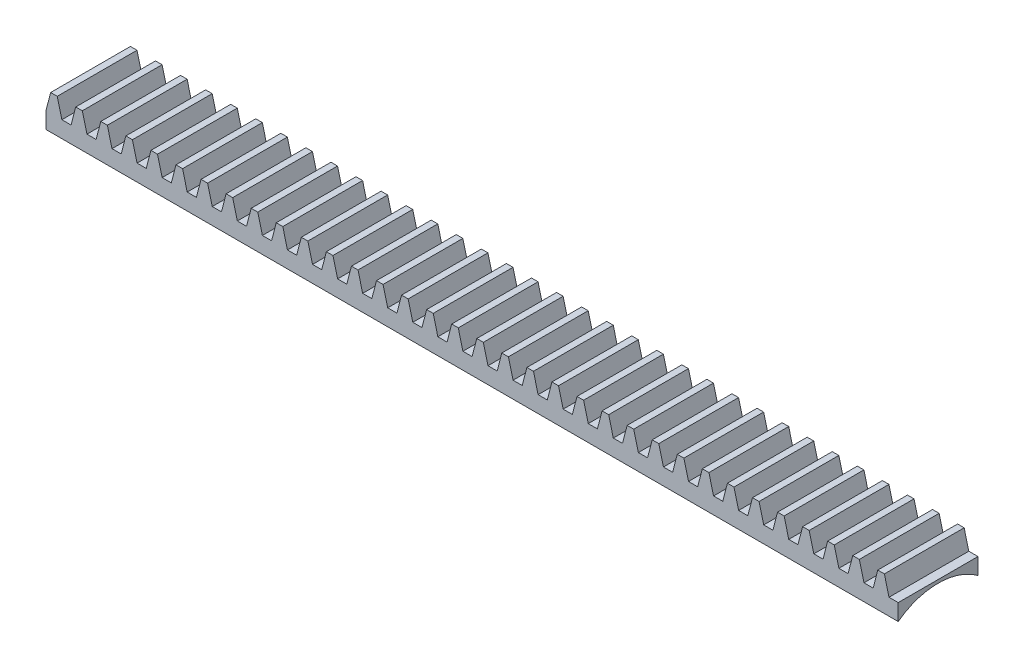
SolidWorks part; units mm, degrees
extrude "Blank" add sketch "BlankSke" against normal blind 10
sketch "BlankSke" plane through (0, 0, 0) normal (0, 0, 1) x (1, 0, 0)
  line L1 (0, 0) -> (110, 0)
  line L2 (0, 0) -> (0, 11)
  line L3 (0, 11) -> (110, 11)
  line L4 (110, 0) -> (110, 11)
  dimension "Length" = 110
  dimension "Blank_height" = 11
ref_plane "Plane1" through (0, 0, 0) normal (0, 0, 1) x (1, 0, 0)
ref_plane "Plane2" through (0, 0, 0) normal (0, 1, 0) x (1, 0, 0)
ref_plane "Plane3" through (0, 0, 0) normal (1, 0, 0) x (0, 0, -1)
sketch "HoldingSke" plane through (0, 0, 0) normal (0, 1, 0) x (1, 0, 0)
  line L0 (0, 0) -> (0.1392, 0.9903)
  line L1 (-15, 0) -> (100, 0) construction
  line L2 (0, 0) -> (-2.1039, 2.3779)
  line L3 (0, 0) -> (-11.863, 4.5341)
  line L4 (0, 0) -> (6.897, 5.1973)
  line L5 (0, 0) -> (-23.7986, -8.8762)
  line L6 (0, 0) -> (-10.5278, -7.1032)
  line L9 (-67.7845, 28.3722) -> (38.7117, 55.914)
  line L10 (-76.2, 3.3779) -> (-66.2, 3.3779)
  line L11 (0, 0) -> (-10, 0)
  line L12 (-76.2, 101.6) -> (-76.162, 101.6)
  line L13 (24.9733, 27.94) -> (52.9518, 28.4284)
  line L14 (24.9733, 27.94) -> (24.9743, 27.94)
  line L15 (24.9733, 27.94) -> (100.4006, 29.5858)
  circle A0 centre (0, 0) radius 19.05
  circle A1 centre (0, 0) radius 5
  circle A2 centre (0, 0) radius 12.7
  dimension "MPH" = 10
  dimension "Diameter" = 38.1
  dimension "Num_teeth" = 37
  dimension "Pitch" = 1
  dimension "Show_teeth" = 998
  dimension "Thickness" = 12.7
  dimension "Ap" = 14.5
  dimension "Pitch_height" = 10
  dimension "Width" = 10
  dimension "Backlash" = 0.038
  dimension "Addendum_fac" = 1
  dimension "Dedendum_fac" = 1.25
  dimension "Clearance_fac" = 0.25
  dimension "Dedendum_add" = 0.001
  dimension "Length" = 110
  dimension "Module" = 1
sketch "TooCutSkeIll" plane through (0, 0, 0) normal (0, 0, 1) x (1, 0, 0)
  line L0 (-1.1503, 10.97) -> (-0.6248, 8.9382)
  line L1 (-0.3818, 8.75) -> (0.3818, 8.75)
  line L2 (0.6248, 8.9382) -> (1.1503, 10.97)
  line L3 (110, 11) -> (0, 11) construction
  line L4 (0, 0) -> (0, 64.897) construction
  line L5 (-13.208, 10) -> (12.954, 10) construction
  line L6 (0, 0) -> (110, 0) construction
  line L7 (0.8994, 10) -> (0.8994, 48.7463) construction
  line L8 (-0.8994, 10) -> (-0.8994, 48.7463) construction
  line L9 (1.189, 11) -> (1.189, 11.0254)
  line L10 (-1.189, 11) -> (-1.189, 11.0254)
  line L11 (-1.189, 11.0254) -> (1.189, 11.0254)
  arc A0 (0.3818, 8.75) -> (0.6248, 8.9382) centre (0.3818, 9.001) ccw
  arc A1 (-0.6248, 8.9382) -> (-0.3818, 8.75) centre (-0.3818, 9.001) ccw
  arc A2 (1.189, 11) -> (1.1503, 10.97) centre (1.189, 10.96) ccw
  arc A3 (-1.1503, 10.97) -> (-1.189, 11) centre (-1.189, 10.96) ccw
  dimension "Pitch_height" = 10
  dimension "Addendum_plus" = 1.0254
  dimension "Pressure_angle" = 14.5
  dimension "Gap_width" = 1.7988
  dimension "Dedendum" = 1.25
extrude "ToothCutIll" [suppressed] cut sketch "TooCutSkeIll" against normal through all
sketch "TooCutSkeSim" plane through (0, 0, 0) normal (0, 0, 1) x (1, 0, 0)
  line L0 (0.5761, 8.75) -> (-0.5761, 8.75)
  line L1 (1.1646, 11.0254) -> (0.5761, 8.75)
  line L2 (0, 17.4625) -> (0, 53.467) construction
  line L3 (1.1646, 11.0254) -> (-1.1646, 11.0254)
  line L6 (-1.1646, 11.0254) -> (-0.5761, 8.75)
  line L9 (-0.8994, 10) -> (0.8994, 10) construction
  line L10 (0, 0) -> (110, 0) construction
  line L11 (0.8994, 10) -> (0.8994, 53.467) construction
  line L12 (-0.8994, 10) -> (-0.8994, 53.467) construction
  dimension "Pitch_height" = 10
  dimension "Addendum_plus" = 1.0254
  dimension "Pressure_angle" = 14.5
  dimension "Gap_width" = 1.7988
  dimension "Dedendum" = 1.25
extrude "ToothCutSim" cut sketch "TooCutSkeSim" against normal through all
pattern_linear "TeethCuts" count 36 spacing 3.1416 along (1, 0, 0) of "ToothCutIll", "ToothCutSim"
sketch "Sketch1" plane through (110, 0, 0) normal (1, 0, 0) x (0, 0, -1)
  line L0 (10, 0) -> (0, 0) construction
  circle A0 centre (5, 0) radius 8.35
  dimension "D1" = 16.7
extrude "Cut-Extrude1" cut sketch "Sketch1" against normal through all both and the other way through all
ref_plane "Plane4" through (77.9637, 8.75, -10) normal (1, 0, 0) x (0, 0, -1)
sketch "Sketch3" plane through (0, 0, -10) normal (0, 0, -1) x (-1, 0, 0)
  line L0 (-110, 6.6875) -> (-110, 11.0569)
  line L2 (0, 6.6875) -> (-110, 6.6875) construction
  line L3 (-0.5761, 8.75) -> (-0.5761, 11)
  line L4 (-110, 11.0569) -> (-107.3903, 11.0569)
  line L5 (-107.3903, 11.0569) -> (-107.3903, 6.6875)
  line L6 (-107.3903, 6.6875) -> (-110, 6.6875)
  line L7 (-0.5761, 11) -> (0, 11)
  line L9 (-0.5761, 8.75) -> (-0.5761, 6.6875)
  line L10 (-0.5761, 6.6875) -> (0, 6.6875)
  line L13 (0, 11) -> (0, 6.6875)
extrude "Cut-Extrude2" cut sketch "Sketch3" against normal blind 10
equation "' \"Module@HoldingSke\" = 6.35"
equation "' \"Num_teeth@HoldingSke\" = 12"
equation "' \"Ap@HoldingSke\" =  20"
equation "' \"Ap@HoldingSke\" = 20"
equation "' \"Width@HoldingSke\" = 0.25 * 25.4"
equation "' \"Show_teeth@HoldingSke\" = 500"
equation "' \"Backlash@HoldingSke\" = 0.009 * 25.4"
equation "' \"Addendum_fac@HoldingSke\" = 1.0"
equation "' \"Dedendum_fac@HoldingSke\" = 1.25"
equation "' \"Dedendum_add@HoldingSke\" = 0.00005 * 25.4"
equation "' \"Clearance_fac@HoldingSke\" = 0.25"
equation "' \"Pitch_height@HoldingSke\" = 1 * 25.4"
equation "' \"Length@HoldingSke\" = 4.71 * 25.4"
equation "\"Pitch@HoldingSke\" = 1 / \"Module@HoldingSke\""
equation "\"MPH@HoldingSke\" = \"Dedendum_fac@HoldingSke\" / \"Pitch@HoldingSke\" + 2 * \"Dedendum_add@HoldingSke\" + 0.002 * 25.4"
equation "\"MPH@HoldingSke\" = ((sgn( \"MPH@HoldingSke\" - \"Pitch_height@HoldingSke\")+1)*( \"MPH@HoldingSke\" - \"Pitch_height@HoldingSke\"))/2 + \"Pitch_height@HoldingSke\""
equation "\"Blank_height@BlankSke\" = \"Pitch_height@HoldingSke\" + \"Addendum_fac@HoldingSke\"  / \"Pitch@HoldingSke\" "
equation "\"Length@BlankSke\" =  \"Length@HoldingSke\""
equation "\"Face_width@Blank\" = \"Width@HoldingSke\""
equation "\"Pressure_angle@TooCutSkeIll\" = \"Ap@HoldingSke\""
equation "\"Addendum_plus@TooCutSkeIll\" =  \"Addendum_fac@HoldingSke\"  / \"Pitch@HoldingSke\" + 0.001 *25.4"
equation "\"Dedendum@TooCutSkeIll\" = \"Dedendum_fac@HoldingSke\"  / \"Pitch@HoldingSke\""
equation "\"Pitch_height@TooCutSkeIll\" =  \"MPH@HoldingSke\""
equation "\"Gap_width@TooCutSkeIll\" = 3.14159265 / 2 / \"Pitch@HoldingSke\" + 6 * \"Backlash@HoldingSke\""
equation "\"Pressure_angle@TooCutSkeSim\" = \"Ap@HoldingSke\""
equation "\"Addendum_plus@TooCutSkeSim\" =  \"Addendum_fac@HoldingSke\"  / \"Pitch@HoldingSke\" + 0.001 * 25.4"
equation "\"Dedendum@TooCutSkeSim\" = \"Dedendum_fac@HoldingSke\"  / \"Pitch@HoldingSke\""
equation "\"Pitch_height@TooCutSkeSim\" =  \"MPH@HoldingSke\""
equation "\"Gap_width@TooCutSkeSim\" = 3.14159265 / 2 / \"Pitch@HoldingSke\" + 6 * \"Backlash@HoldingSke\""
equation "\"Root_fillet@TooCutSkeIll\" = \"Clearance_fac@HoldingSke\" / \"Pitch@HoldingSke\" + \"Dedendum_add@HoldingSke\""
equation "\"Break_rad@TooCutSkeIll\" = 0.02 / \"Pitch@HoldingSke\" * 2"
equation "\"Linear_pitch@TeethCuts\" = 3.14159265 / \"Pitch@HoldingSke\""
equation "\"Num_teeth@HoldingSke\" = int( ( \"Length@HoldingSke\" + 0 ) / (3.14159265 / \"Pitch@HoldingSke\")) + 0.9999  + 1"
equation " \"Num_teeth@TeethCuts\" = int( \"Show_teeth@HoldingSke\" ) + 1"
equation " \"Num_teeth@TeethCuts\" = ((sgn( \"Num_teeth@TeethCuts\" - \"Num_teeth@HoldingSke\" )-1)*( \"Num_teeth@TeethCuts\" - \"Num_teeth@HoldingSke\" ))/-2+ \"Num_teeth@HoldingSke\""
equation " \"Num_teeth@TeethCuts\" = ((sgn( \"Num_teeth@TeethCuts\" - 2.0)+1)*( \"Num_teeth@TeethCuts\" - 2.0))/2 +2.0"
